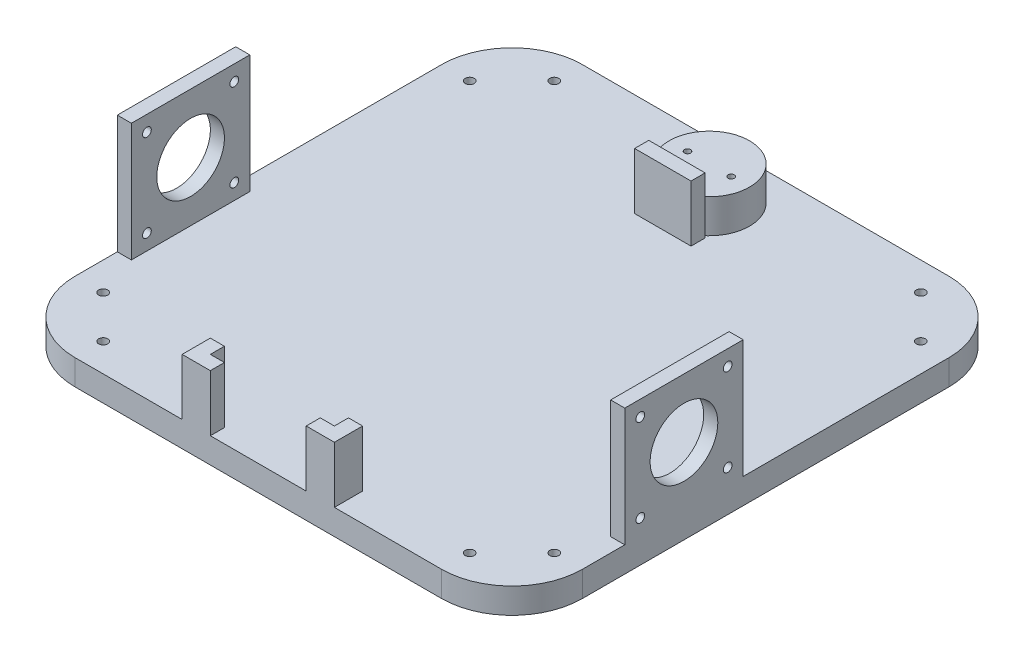
SolidWorks part; units mm, degrees
ref_plane "Front Plane" through (0, 0, 0) normal (0, 0, 1) x (1, 0, 0)
ref_plane "Top Plane" through (0, 0, 0) normal (0, 1, 0) x (1, 0, 0)
ref_plane "Right Plane" through (0, 0, 0) normal (1, 0, 0) x (0, 0, -1)
sketch "Sketch1" plane through (0, 0, 0) normal (0, 1, 0) x (1, 0, 0)
  line L1 (-65, -90) -> (65, -90)
  line L2 (-90, -65) -> (-90, 65)
  line L3 (-65, 90) -> (65, 90)
  line L4 (90, -65) -> (90, 65)
  arc A0 (-90, 65) -> (-65, 90) centre (-65, 65) cw
  arc A1 (65, 90) -> (90, 65) centre (65, 65) cw
  arc A2 (90, -65) -> (65, -90) centre (65, -65) cw
  arc A3 (-65, -90) -> (-90, -65) centre (-65, -65) cw
  point P4 (-90, 0)
  point P6 (0, 90)
  dimension "D3" = 25
  dimension "D1" = 180
  dimension "D2" = 180
extrude "Plate" add sketch "Sketch1" along normal blind 9
sketch "Sketch3" plane through (0, 9, 0) normal (0, 1, 0) x (1, 0, 0)
  line L0 (-65, 90) -> (-65, -90) construction
  line L1 (65, 90) -> (65, -90) construction
  line L2 (-90, 65) -> (90, 65) construction
  line L3 (-90, -65) -> (90, -65) construction
  circle A0 centre (-65, 80) radius 1.6
  circle A1 centre (-80, 65) radius 1.6
  circle A2 centre (80, 65) radius 1.6
  circle A3 centre (80, -65) radius 1.6
  circle A4 centre (65, 80) radius 1.6
  circle A5 centre (65, -80) radius 1.6
  circle A6 centre (-65, -80) radius 1.6
  circle A7 centre (-80, -65) radius 1.6
  dimension "D1" = 3.2
  dimension "D2" = 15
  dimension "D3" = 15
  dimension "D4" = 15
  dimension "D5" = 15
  dimension "D6" = 15
  dimension "D7" = 15
  dimension "D8" = 15
  dimension "D9" = 15
extrude "Hex Holes" cut sketch "Sketch3" against normal through all
sketch "Sketch4" plane through (0, 9, 0) normal (0, 1, 0) x (1, 0, 0)
  line L0 (-22, -85) -> (-17, -85)
  line L1 (-17, -85) -> (-17, -90)
  line L2 (-17, -90) -> (-27, -90)
  line L3 (-27, -90) -> (-27, -80)
  line L4 (-27, -80) -> (-22, -80)
  line L5 (-22, -80) -> (-22, -85)
  line L6 (17, -85) -> (22, -85)
  line L7 (22, -85) -> (22, -80)
  line L8 (22, -80) -> (27, -80)
  line L9 (27, -80) -> (27, -90)
  line L10 (27, -90) -> (17, -90)
  line L11 (17, -90) -> (17, -85)
  line L12 (-90, -65) -> (-90, 65) construction
  line L13 (-65, -90) -> (65, -90) construction
  line L14 (-65, 90) -> (65, 90) construction
  line L15 (-10, 53.5) -> (10, 53.5)
  line L16 (-10, 53.5) -> (-10, 58.5)
  line L17 (-10, 58.5) -> (10, 58.5)
  line L18 (10, 53.5) -> (10, 58.5)
  point P20 (0, 58.5)
  point P23 (0, 90)
  dimension "D1" = 44
  dimension "D2" = 5
  dimension "D3" = 63
  dimension "D4" = 0
  dimension "D5" = 138.5
  dimension "D6" = 5
  dimension "D7" = 20
extrude "Battery Holder" add sketch "Sketch4" along normal blind 20
sketch "Sketch5" plane through (-90, 0, 0) normal (-1, 0, 0) x (0, 0, 1)
  line L0 (-65, 9) -> (65, 9) construction
  line L1 (50, 9) -> (8, 9)
  line L2 (50, 9) -> (50, 51)
  line L3 (50, 51) -> (8, 51)
  line L4 (8, 9) -> (8, 51)
  line L5 (65, 9) -> (65, 0) construction
  circle A0 centre (29, 30) radius 12
  circle A1 centre (13.5, 45.5) radius 1.55
  circle A2 centre (44.5, 45.5) radius 1.55
  circle A3 centre (44.5, 14.5) radius 1.55
  circle A4 centre (13.5, 14.5) radius 1.55
  point P11 (29, 51)
  point P20 (8, 30)
  dimension "D4" = 24
  dimension "D5" = 3.1
  dimension "D1" = 42
  dimension "D2" = 42
  dimension "D3" = 15
  dimension "D6" = 5.5
  dimension "D7" = 5.5
  dimension "D8" = 5.5
  dimension "D9" = 5.5
extrude "Boss-Extrude2" add sketch "Sketch5" against normal blind 5
sketch "Sketch6" plane through (90, 0, 0) normal (1, 0, 0) x (0, 0, -1)
  line L0 (-8, 9) -> (-50, 9)
  line L1 (-8, 9) -> (-8, 51)
  line L2 (-8, 51) -> (-50, 51)
  line L3 (-50, 9) -> (-50, 51)
  line L4 (-65, 9) -> (-65, 0) construction
  line L5 (-65, 9) -> (65, 9) construction
  circle A0 centre (-29, 30) radius 12
  circle A1 centre (-44.5, 45.5) radius 1.55
  circle A2 centre (-13.5, 45.5) radius 1.55
  circle A3 centre (-13.5, 14.5) radius 1.55
  circle A4 centre (-44.5, 14.5) radius 1.55
  point P7 (-29, 51)
  point P15 (-50, 30)
  dimension "D6" = 3.1
  dimension "D7" = 24
  dimension "D1" = 15
  dimension "D2" = 42
  dimension "D3" = 42
  dimension "D4" = 5.5
  dimension "D5" = 5.5
  dimension "D8" = 5.5
  dimension "D9" = 5.5
extrude "Boss-Extrude3" add sketch "Sketch6" against normal blind 5
sketch "Sketch8" plane through (0, 9, 0) normal (0, 1, 0) x (1, 0, 0)
  line L0 (-65, 90) -> (65, 90) construction
  line L1 (0, 90) -> (0, -90) construction
  line L2 (-65, -90) -> (65, -90) construction
  circle A0 centre (0, 70) radius 14.25
  dimension "D2" = 28.5
  dimension "D1" = 20
extrude "Boss-Extrude4" add sketch "Sketch8" along normal blind 12
sketch "Sketch7" plane through (0, 0, 0) normal (0, -1, 0) x (1, 0, 0)
  line L0 (-65, -90) -> (65, -90) construction
  line L1 (0, 90) -> (0, -90) construction
  line L2 (-65, 90) -> (65, 90) construction
  circle A0 centre (0, -70) radius 11.75
  dimension "D2" = 23.5
  dimension "D1" = 20
extrude "Cut-Extrude1" cut sketch "Sketch7" against normal blind 10.6
sketch "Sketch2" plane through (0, 9, 0) normal (0, 1, 0) x (1, 0, 0)
  line L0 (-7.747, 70) -> (7.747, 70) construction
  line L1 (0, 90) -> (0, 70) construction
  line L2 (-65, 90) -> (65, 90) construction
  circle A1 centre (-7.747, 70) radius 1.09
  circle A2 centre (7.747, 70) radius 1.09
  dimension "D3" = 2.18
  dimension "D1" = 15.494
  dimension "D2" = 20
extrude "Caster Holes" cut sketch "Sketch2" against normal through all both and the other way through all
